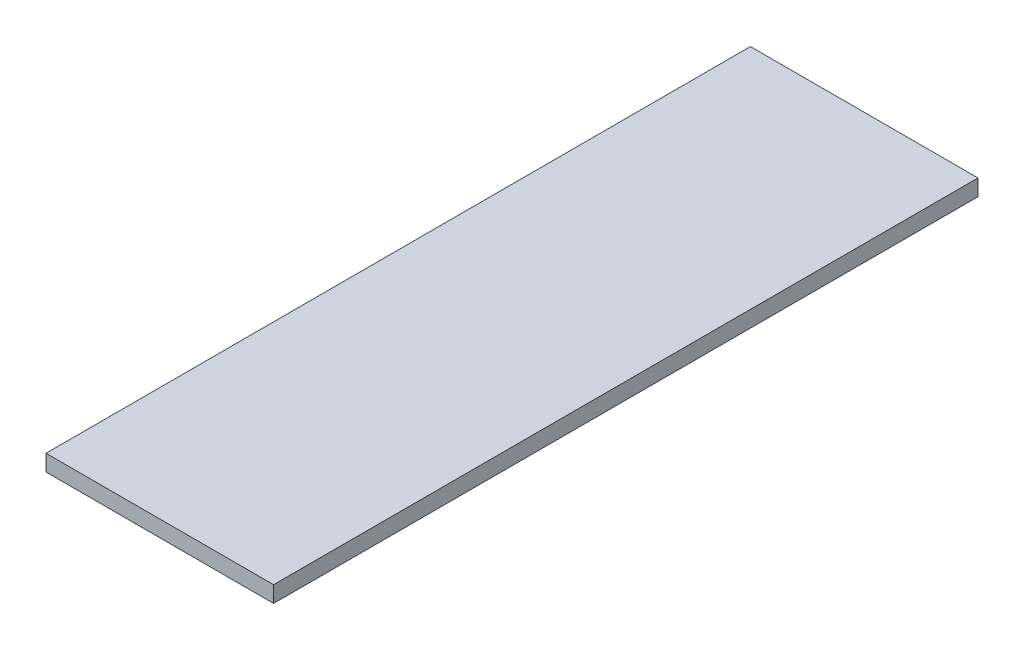
SolidWorks part; units mm, degrees
ref_plane "Front Plane" through (0, 0, 0) normal (0, 0, 1) x (1, 0, 0)
ref_plane "Top Plane" through (0, 0, 0) normal (0, 1, 0) x (1, 0, 0)
ref_plane "Right Plane" through (0, 0, 0) normal (1, 0, 0) x (0, 0, -1)
sketch "Sketch1" plane through (0, 0, 0) normal (0, 1, 0) x (1, 0, 0)
  line L1 (-10.5, -32.5) -> (10.5, -32.5)
  line L2 (-10.5, -32.5) -> (-10.5, 32.5)
  line L3 (-10.5, 32.5) -> (10.5, 32.5)
  line L4 (10.5, -32.5) -> (10.5, 32.5)
  line L5 (-10.5, -32.5) -> (10.5, 32.5) construction
  line L6 (-10.5, 32.5) -> (10.5, -32.5) construction
  point P0 (0, 0)
  dimension "D1" = 21
  dimension "D2" = 65
extrude "Boss-Extrude1" add sketch "Sketch1" along normal blind 1.5
